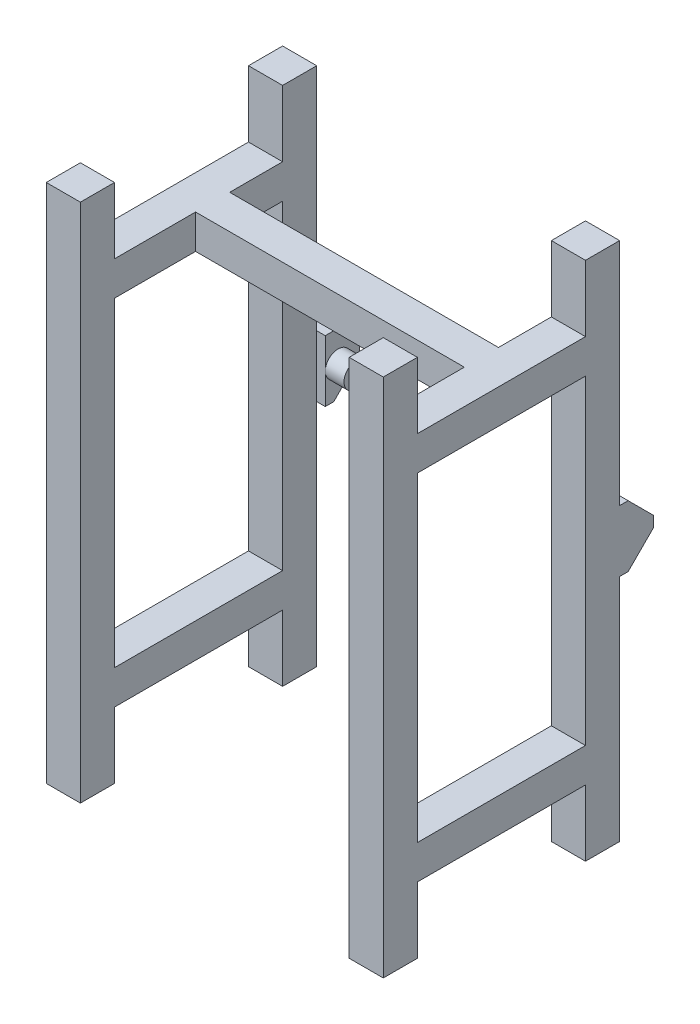
SolidWorks part; units mm, degrees
ref_plane "Front Plane" through (0, 0, 0) normal (0, 0, 1) x (1, 0, 0)
ref_plane "Top Plane" through (0, 0, 0) normal (0, 1, 0) x (1, 0, 0)
ref_plane "Right Plane" through (0, 0, 0) normal (1, 0, 0) x (0, 0, -1)
sketch "Sketch1" plane through (0, 0, 0) normal (0, 1, 0) x (1, 0, 0)
  line L0 (0, 98.5) -> (0, -98.5) construction
  line L1 (-157.5, -98.5) -> (157.5, -98.5) construction
  line L2 (-157.5, -98.5) -> (-157.5, 98.5) construction
  line L3 (-157.5, 98.5) -> (157.5, 98.5) construction
  line L4 (157.5, -98.5) -> (157.5, 98.5) construction
  line L5 (-157.5, -98.5) -> (157.5, 98.5) construction
  line L6 (-157.5, 98.5) -> (157.5, -98.5) construction
  line L7 (-157.5, 98.5) -> (-197.5, 98.5)
  line L8 (-157.5, 98.5) -> (-157.5, 138.5)
  line L9 (-157.5, 138.5) -> (-197.5, 138.5)
  line L10 (-197.5, 98.5) -> (-197.5, 138.5)
  line L11 (-157.5, 0) -> (157.5, 0) construction
  line L12 (157.5, 138.5) -> (197.5, 138.5)
  line L13 (197.5, 98.5) -> (197.5, 138.5)
  line L14 (157.5, 98.5) -> (197.5, 98.5)
  line L15 (157.5, 98.5) -> (157.5, 138.5)
  line L16 (157.5, -98.5) -> (157.5, -138.5)
  line L17 (157.5, -98.5) -> (197.5, -98.5)
  line L18 (197.5, -98.5) -> (197.5, -138.5)
  line L19 (157.5, -138.5) -> (197.5, -138.5)
  line L20 (-157.5, -138.5) -> (-197.5, -138.5)
  line L21 (-197.5, -98.5) -> (-197.5, -138.5)
  line L22 (-157.5, -98.5) -> (-197.5, -98.5)
  line L23 (-157.5, -98.5) -> (-157.5, -138.5)
  point P0 (0, 0)
  dimension "D1" = 40
  dimension "D2" = 40
  dimension "D3" = 197
  dimension "D4" = 315
extrude "Boss-Extrude1" add sketch "Sketch1" along normal blind 610
sketch "Sketch2" plane through (0, 0, 98.5) normal (0, 0, -1) x (-1, 0, 0)
  line L0 (157.5, 610) -> (157.5, 0) construction
  line L1 (157.5, 77.5) -> (197.5, 77.5)
  line L2 (157.5, 77.5) -> (157.5, 117.5)
  line L3 (157.5, 117.5) -> (197.5, 117.5)
  line L4 (197.5, 77.5) -> (197.5, 117.5)
  line L5 (197.5, 610) -> (197.5, 0) construction
  line L6 (0, 0) -> (0, 609.4131) construction
  line L7 (197.5, 305) -> (-198.2487, 305) construction
  line L8 (-157.5, 117.5) -> (-197.5, 117.5)
  line L9 (-197.5, 77.5) -> (-197.5, 117.5)
  line L10 (-157.5, 77.5) -> (-197.5, 77.5)
  line L11 (-157.5, 77.5) -> (-157.5, 117.5)
  line L12 (-157.5, 532.5) -> (-157.5, 492.5)
  line L13 (-157.5, 532.5) -> (-197.5, 532.5)
  line L14 (-197.5, 532.5) -> (-197.5, 492.5)
  line L15 (-157.5, 492.5) -> (-197.5, 492.5)
  line L16 (157.5, 492.5) -> (197.5, 492.5)
  line L17 (197.5, 532.5) -> (197.5, 492.5)
  line L18 (157.5, 532.5) -> (197.5, 532.5)
  line L19 (157.5, 532.5) -> (157.5, 492.5)
  point P25 (177.5, 117.5)
  dimension "D1" = 375
  dimension "D2" = 40
extrude "Boss-Extrude2" add sketch "Sketch2" along normal up to next (237 mm away)
sketch "Sketch3" plane through (-157.5, 0, 0) normal (1, 0, 0) x (0, 0, -1)
  line L0 (98.5, 532.5) -> (-98.5, 532.5) construction
  line L1 (-3.5, 532.5) -> (36.5, 532.5)
  line L2 (-3.5, 532.5) -> (-3.5, 492.5)
  line L3 (-3.5, 492.5) -> (36.5, 492.5)
  line L4 (36.5, 532.5) -> (36.5, 492.5)
  line L5 (98.5, 492.5) -> (-98.5, 492.5) construction
  line L6 (-98.5, 610) -> (-98.5, 532.5) construction
  dimension "D1" = 40
  dimension "D2" = 95
extrude "Boss-Extrude3" add sketch "Sketch3" along normal up to next
sketch "Sketch4" plane through (0, 0, -138.5) normal (0, 0, -1) x (-1, 0, 0)
  line L0 (197.5, 610) -> (197.5, 0) construction
  line L1 (197.5, 269) -> (147.5, 269)
  line L2 (197.5, 269) -> (197.5, 341)
  line L3 (197.5, 341) -> (147.5, 341)
  line L4 (147.5, 269) -> (147.5, 341)
  point P6 (197.5, 305)
  point P7 (197.5, 305)
  dimension "D1" = 50
  dimension "D2" = 72
extrude "Boss-Extrude4" add sketch "Sketch4" along normal blind 40
chamfer "Chamfer1" distance 30 2 edges at (-172.5, 269, -178.5) (-172.5, 341, -178.5)
sketch "Sketch5" plane through (-147.5, 0, 0) normal (1, 0, 0) x (0, 0, -1)
  line L0 (138.5, 305) -> (178.5, 305) construction
  line L1 (138.5, 341) -> (138.5, 269) construction
  line L2 (178.5, 311) -> (178.5, 299) construction
  circle A0 centre (153.5, 305) radius 15
  dimension "D1" = 30
extrude "Boss-Extrude5" add sketch "Sketch5" along normal blind 22 contours A0
ref_plane "Plane1" through (0, 0, 0) normal (1, 0, 0) x (0, 0, -1)
mirror "Mirror1" about plane through (0, 0, 0) normal (1, 0, 0) of "Boss-Extrude5", "Chamfer1", "Boss-Extrude4"
